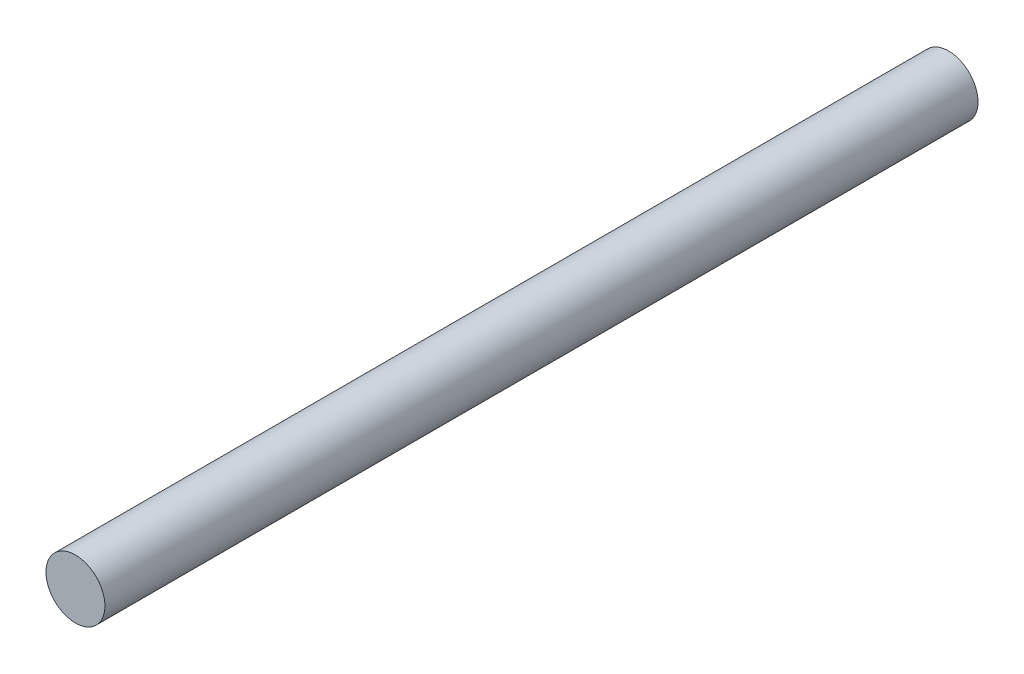
SolidWorks part; units mm, degrees
material "Liga 1060"
ref_plane "Plano frontal" through (0, 0, 0) normal (0, 0, 1) x (1, 0, 0)
ref_plane "Plano superior" through (0, 0, 0) normal (0, 1, 0) x (1, 0, 0)
ref_plane "Plano direito" through (0, 0, 0) normal (1, 0, 0) x (0, 0, -1)
sketch "Esboço1" plane through (0, 0, 0) normal (0, 0, 1) x (1, 0, 0)
  circle A0 centre (0, 0) radius 3.175
  dimension "D1" = 6.35
extrude "Ressalto-extrusão1" add sketch "Esboço1" along normal blind 94
